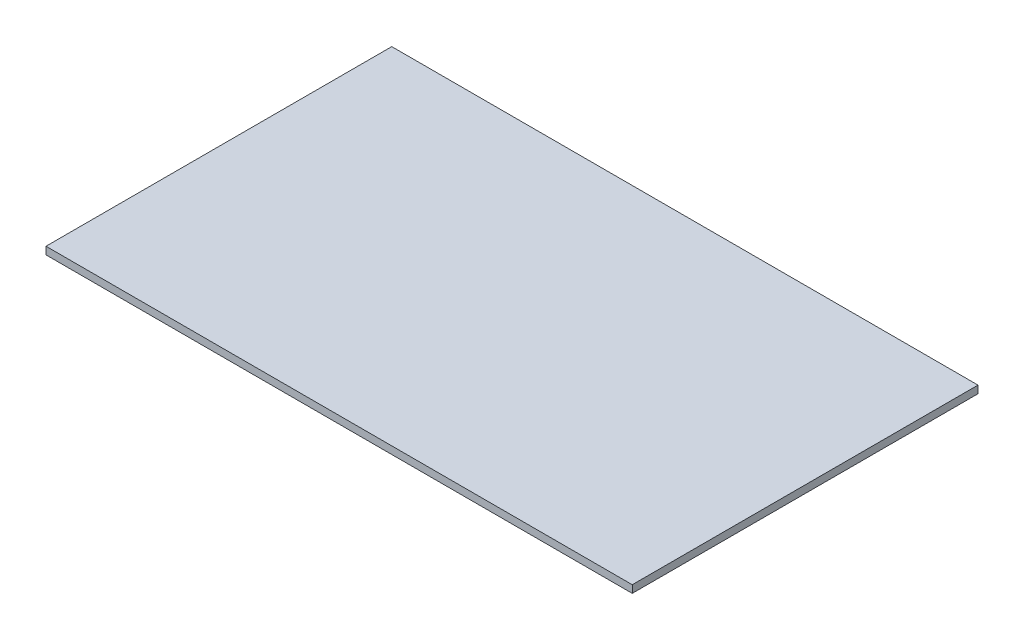
SolidWorks part; units mm, degrees
ref_plane "Front Plane" through (0, 0, 0) normal (0, 0, 1) x (1, 0, 0)
ref_plane "Top Plane" through (0, 0, 0) normal (0, 1, 0) x (1, 0, 0)
ref_plane "Right Plane" through (0, 0, 0) normal (1, 0, 0) x (0, 0, -1)
sketch "Sketch1" plane through (0, 0, 0) normal (0, 1, 0) x (1, 0, 0)
  line L1 (-39, 23) -> (39, 23)
  line L2 (-39, 23) -> (-39, -23)
  line L3 (-39, -23) -> (39, -23)
  line L4 (39, 23) -> (39, -23)
  line L5 (-39, 23) -> (39, -23) construction
  line L6 (-39, -23) -> (39, 23) construction
  point P0 (0, 0)
  dimension "D1" = 78
  dimension "D2" = 46
extrude "Boss-Extrude1" add sketch "Sketch1" along normal blind 1
